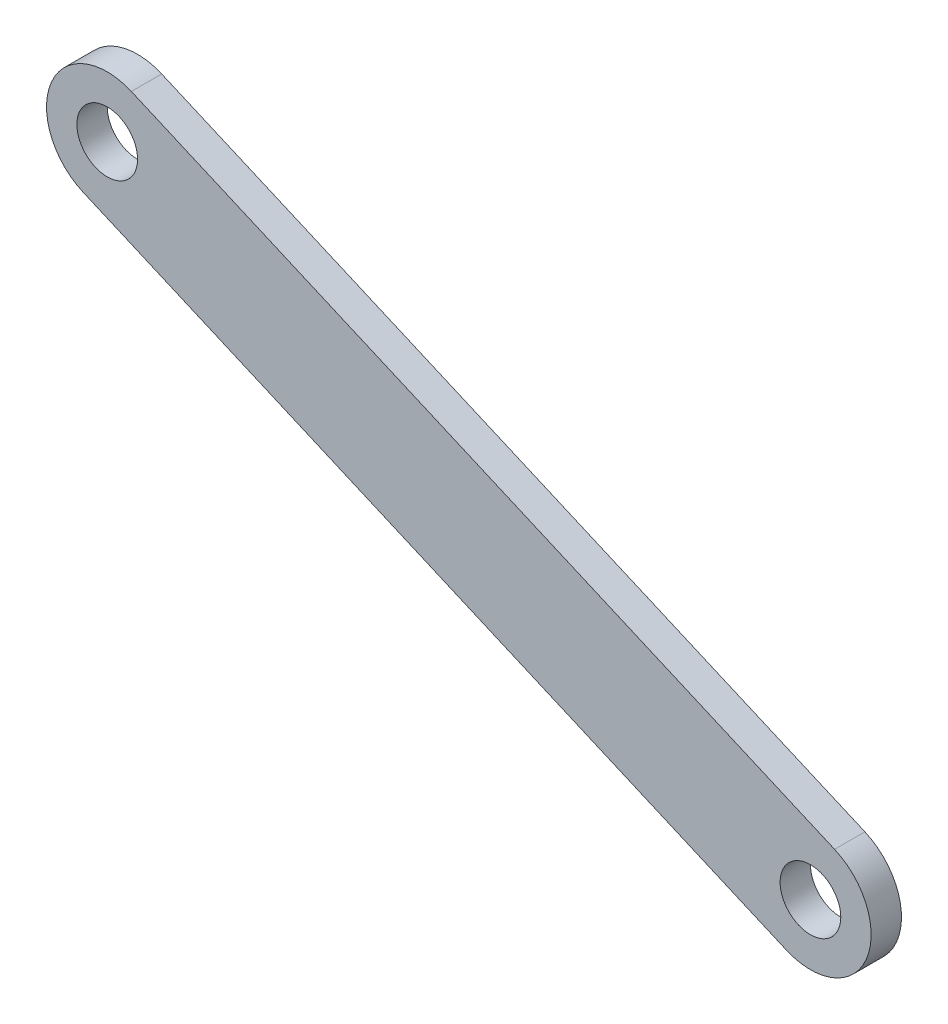
SolidWorks part; units mm, degrees
ref_plane "Front" through (0, 0, 0) normal (0, 0, 1) x (1, 0, 0)
ref_plane "Top" through (0, 0, 0) normal (0, 1, 0) x (1, 0, 0)
ref_plane "Right" through (0, 0, 0) normal (1, 0, 0) x (0, 0, -1)
sketch "Sketch1" plane through (0, 0, 0) normal (0, 0, 1) x (1, 0, 0)
  line L0 (-74.7944, 8.1432) -> (-38, -7.8) construction
  line L1 (-73.532, 11.0564) -> (-36.7377, -4.8867)
  line L2 (-76.0567, 5.2299) -> (-39.2623, -10.7133)
  arc A0 (-73.532, 11.0564) -> (-76.0567, 5.2299) centre (-74.7944, 8.1432) ccw
  arc A1 (-39.2623, -10.7133) -> (-36.7377, -4.8867) centre (-38, -7.8) ccw
  circle A2 centre (-38, -7.8) radius 1.5875
  circle A3 centre (-74.7944, 8.1432) radius 1.5875
  point P4 (-56.3972, 0.1716)
  dimension "D1" = 3.175
  dimension "D2" = 6.35
extrude "Boss-Extrude1" add sketch "Sketch1" against normal blind 1.5875
